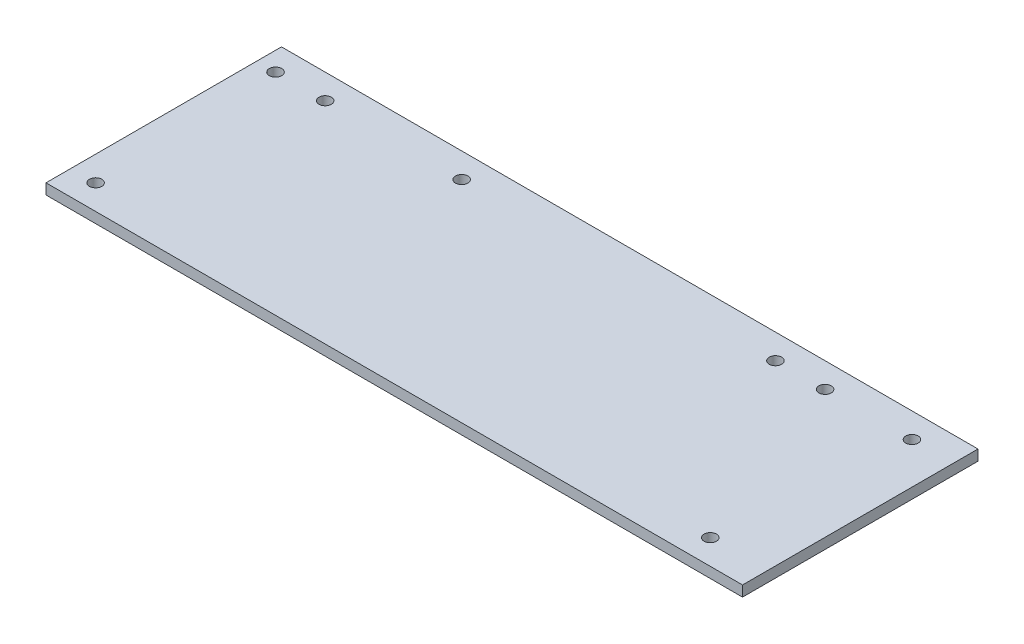
SolidWorks part; units mm, degrees
ref_plane "Front Plane" through (0, 0, 0) normal (0, 0, 1) x (1, 0, 0)
ref_plane "Top Plane" through (0, 0, 0) normal (0, 1, 0) x (1, 0, 0)
ref_plane "Right Plane" through (0, 0, 0) normal (1, 0, 0) x (0, 0, -1)
sketch "Sketch1" plane through (0, 0, 0) normal (0, 1, 0) x (1, 0, 0)
  line L1 (-165.481, -47.5361) -> (165.481, -47.5361)
  line L2 (-165.481, -47.5361) -> (-165.481, 47.5361)
  line L3 (-165.481, 47.5361) -> (165.481, 47.5361)
  line L4 (165.481, -47.5361) -> (165.481, 47.5361)
  line L5 (-165.481, -47.5361) -> (165.481, 47.5361) construction
  line L6 (-165.481, 47.5361) -> (165.481, -47.5361) construction
  line L15 (165.481, -47.5361) -> (114.8334, -47.5361)
  line L16 (165.481, -47.5361) -> (165.481, -42.1259)
  line L19 (-165.481, 47.5361) -> (-190.881, 47.5361)
  line L20 (-165.481, 47.5361) -> (-165.481, -47.5361)
  line L21 (-165.481, -47.5361) -> (-190.881, -47.5361)
  line L22 (-190.881, 47.5361) -> (-190.881, -47.5361)
  line L23 (-190.881, -47.5361) -> (165.481, -47.5361)
  line L24 (-190.881, -47.5361) -> (-190.881, -72.9361)
  line L25 (-190.881, -72.9361) -> (165.481, -72.9361)
  line L26 (165.481, -47.5361) -> (165.481, -72.9361)
  line L34 (86.7283, -47.6885) -> (91.8337, -47.6885) construction
  line L35 (86.5759, -47.5361) -> (91.9861, -47.5361)
  line L36 (86.5759, -47.5361) -> (86.5759, -60.2361)
  line L37 (86.5759, -60.2361) -> (91.9861, -60.2361)
  line L38 (91.9861, -47.5361) -> (91.9861, -60.2361)
  line L39 (91.8337, -47.6885) -> (91.8337, -60.0837) construction
  line L40 (86.7283, -60.0837) -> (91.8337, -60.0837) construction
  line L41 (86.7283, -47.6885) -> (86.7283, -60.0837) construction
  line L42 (-73.3069, 47.5361) -> (-73.3069, -42.1259)
  line L44 (62.5475, -42.1259) -> (62.5475, 47.5361)
  circle A0 centre (-155.829, 34.8361) radius 3.175
  circle A1 centre (-86.0069, 34.8361) radius 3.175
  circle A2 centre (99.949, 34.8361) radius 3.175
  circle A3 centre (144.399, 34.8361) radius 3.175
  circle A4 centre (-181.229, 34.8361) radius 3.175
  circle A5 centre (-178.181, -60.2361) radius 3.175
  circle A6 centre (136.271, -60.2361) radius 3.175
  circle A7 centre (74.549, 34.8361) radius 3.175
  dimension "D10" = 69.8221
  dimension "D18" = 25.4
  dimension "D22" = 6.35
  dimension "D23" = 12.7
  dimension "D25" = 12.7
  dimension "D27" = 12.7
  dimension "D6" = 25.4
  dimension "D1" = 330.962
  dimension "D2" = 95.0722
  dimension "D4" = 21.082
  dimension "D5" = 44.45
  dimension "D11" = 9.652
  dimension "D14" = 12.7
  dimension "D15" = 12.7
  dimension "D16" = 12.7
  dimension "D17" = 12.7
  dimension "D19" = 25.4
  dimension "D20" = 12.7
  dimension "D21" = 25.4
  dimension "D24" = 12.7
  dimension "D26" = 29.21
  dimension "D35" = 12.7
  dimension "D36" = 5.4102
  dimension "D38" = 0.1524
extrude "Boss-Extrude1" add sketch "Sketch1" along normal blind 5.4102
